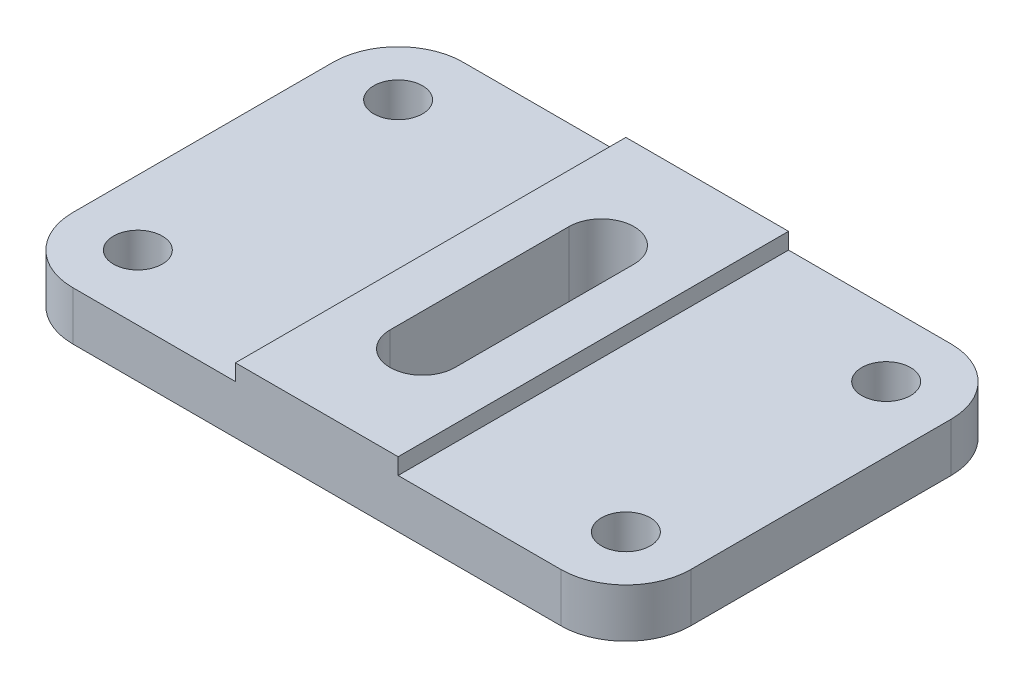
SolidWorks part; units mm, degrees
ref_plane "Ön Düzlem" through (0, 0, 0) normal (0, 0, 1) x (1, 0, 0)
ref_plane "Üst Düzlem" through (0, 0, 0) normal (0, 1, 0) x (1, 0, 0)
ref_plane "Sağ Düzlem" through (0, 0, 0) normal (1, 0, 0) x (0, 0, -1)
sketch "Çizim1" plane through (0, 0, 0) normal (0, 0, 1) x (1, 0, 0)
  line L0 (-23.3406, 3.4756) -> (46.6594, 3.4756)
  line L1 (-143.3406, 3.4756) -> (-73.3406, 3.4756)
  line L2 (-143.3406, 3.4756) -> (-143.3406, -11.5244)
  line L3 (-143.3406, -11.5244) -> (46.6594, -11.5244)
  line L4 (46.6594, 3.4756) -> (46.6594, -11.5244)
  line L5 (-73.3406, 8.4756) -> (-23.3406, 8.4756)
  line L6 (-73.3406, 8.4756) -> (-73.3406, 3.4756)
  line L8 (-23.3406, 8.4756) -> (-23.3406, 3.4756)
  point P4 (-57.0967, 5.1585)
  dimension "D1" = 190
  dimension "D2" = 70
  dimension "D3" = 50
  dimension "D4" = 15
  dimension "D5" = 5
  dimension "D6" = 5
extrude "Yükseklik-Ekstrüzyon1" add sketch "Çizim1" along normal blind 120
fillet "Radyus1" radius 20 4 edges at (46.6594, -4.0244, 120) (46.6594, -4.0244, 0) (-143.3406, -4.0244, 120) (-143.3406, -4.0244, 0)
sketch "Çizim2" plane through (0, 8.4756, 0) normal (0, 1, 0) x (1, 0, 0)
  line L0 (-48.3406, -32.5) -> (-48.3406, -87.5) construction
  line L1 (-38.3406, -32.5) -> (-38.3406, -87.5)
  line L2 (-58.3406, -32.5) -> (-58.3406, -87.5)
  line L5 (-23.3406, 0) -> (-73.3406, 0) construction
  line L6 (-23.3406, -120) -> (-73.3406, -120) construction
  arc A0 (-38.3406, -32.5) -> (-58.3406, -32.5) centre (-48.3406, -32.5) ccw
  arc A1 (-58.3406, -87.5) -> (-38.3406, -87.5) centre (-48.3406, -87.5) ccw
  point P2 (-48.3406, -60)
  point P7 (0, 0)
  dimension "D2" = 10
  dimension "D3" = 60
  dimension "D1" = 55
  dimension "D4" = 60
extrude "Kes-Ekstrüzyon1" cut sketch "Çizim2" against normal through all
sketch "Çizim3" plane through (0, 3.4756, 0) normal (0, 1, 0) x (1, 0, 0)
  line L0 (-48.3406, -48.1899) -> (-48.3406, -145.2339) construction
  circle A0 centre (-123.3406, -20) radius 7.5
  circle A1 centre (-123.3406, -100) radius 7.5
  circle A2 centre (26.6594, -100) radius 7.5
  circle A3 centre (26.6594, -20) radius 7.5
  dimension "D1" = 15
  dimension "D2" = 15
extrude "Kes-Ekstrüzyon2" cut sketch "Çizim3" against normal through all contours A3 | A2 | A1 | A0
